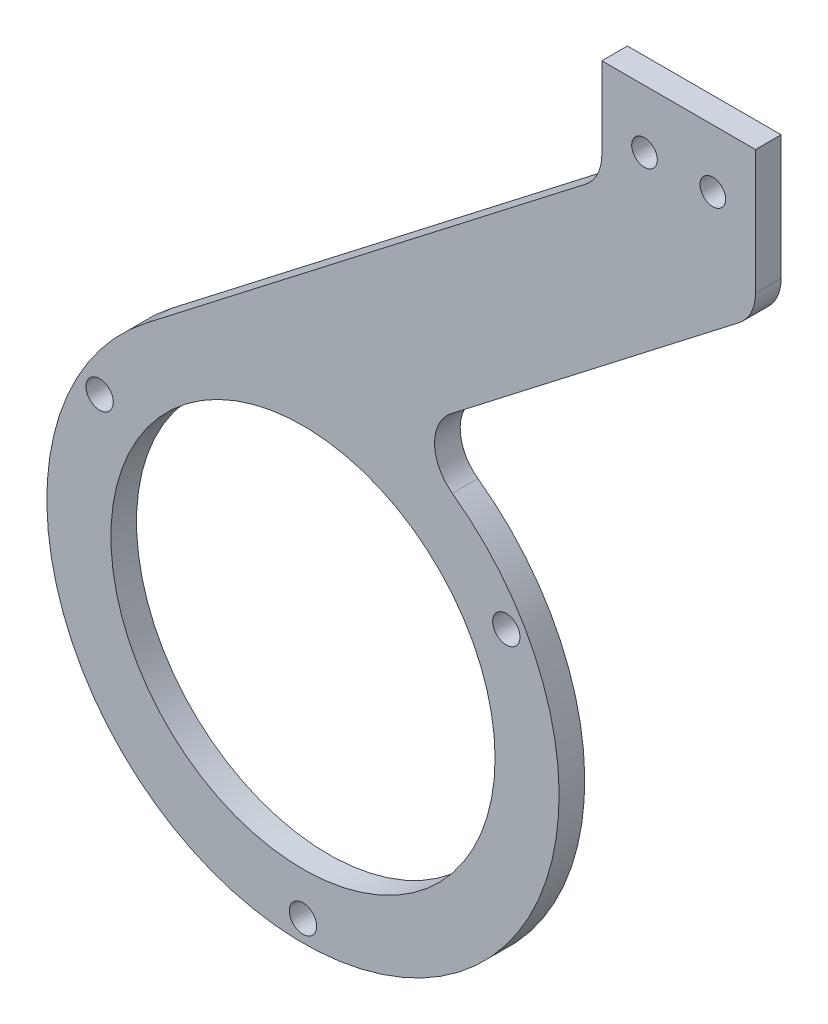
SolidWorks part; units mm, degrees
material "A-玻璃纤维"
ref_plane "前视基准面" through (0, 0, 0) normal (0, 0, 1) x (1, 0, 0)
ref_plane "上视基准面" through (0, 0, 0) normal (0, 1, 0) x (1, 0, 0)
ref_plane "右视基准面" through (0, 0, 0) normal (1, 0, 0) x (0, 0, -1)
sketch "草图1" plane through (0, 0, 0) normal (0, 0, 1) x (1, 0, 0)
  line L0 (0, 0) -> (0, -27.5) construction
  circle A0 centre (0, 0) radius 22.5
  circle A1 centre (0, 0) radius 30
  circle A2 centre (0, 0) radius 27.5 construction
  circle A3 centre (23.8157, 13.75) radius 1.6
  circle A4 centre (0, -27.5) radius 1.6
  circle A5 centre (-23.8157, 13.75) radius 1.6
  point P14 (0, 0)
  dimension "D1" = 45
  dimension "D2" = 60
  dimension "D3" = 55
  dimension "D4" = 3.2
  dimension "D5" = 3
extrude "凸台-拉伸1" add sketch "草图1" along normal blind 3
sketch "草图4" plane through (0, 0, 3) normal (0, 0, 1) x (1, 0, 0)
  line L0 (-18.355, 23.7296) -> (35, 65)
  line L1 (35, 65) -> (35, 77)
  line L2 (35, 77) -> (53, 77)
  line L3 (53, 77) -> (53, 59.9595)
  line L4 (53, 59.9595) -> (11.373, 27.7607)
  line L5 (-18.355, 23.7296) -> (-0.7939, 26.1109)
  line L6 (-950.3336, 65) -> (49049.6664, 65) construction
  line L7 (1.1352, 26.3725) -> (11.373, 27.7607)
  line L8 (-959.0453, 70.2) -> (49040.9547, 70.2) construction
  circle A0 centre (0, 0) radius 30 construction
  arc A1 (1.1352, 26.3725) -> (-0.7939, 26.1109) centre (0, 27.5) ccw
  circle A2 centre (40, 70.2) radius 1.5
  circle A3 centre (48, 70.2) radius 1.5
  dimension "D6" = 3.2
  dimension "D9" = 3
  dimension "D10" = 5
  dimension "D1" = 15
  dimension "D2" = 18
  dimension "D3" = 65
  dimension "D4" = 35
  dimension "D5" = 12
  dimension "D7" = 6.8
  dimension "D8" = 8
extrude "凸台-拉伸3" add sketch "草图4" against normal blind 3
fillet "圆角1" radius 5 1 edges at (11.373, 27.7607, 1.5)
fillet "圆角2" radius 5 2 edges at (53, 59.9595, 1.5) (35, 65, 1.5)
